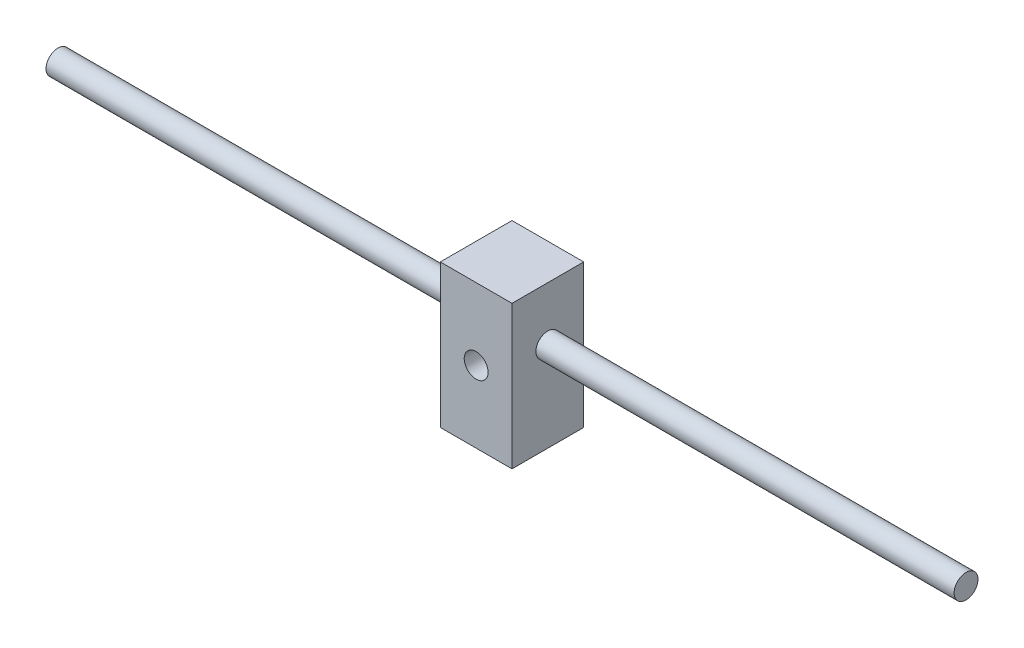
SolidWorks part; units mm, degrees
ref_plane "Спереди" through (0, 0, 0) normal (0, 0, 1) x (1, 0, 0)
ref_plane "Сверху" through (0, 0, 0) normal (0, 1, 0) x (1, 0, 0)
ref_plane "Справа" through (0, 0, 0) normal (1, 0, 0) x (0, 0, -1)
other "Configuration Table"
sketch "Эскиз1" plane through (0, 0, 0) normal (0, 0, 1) x (1, 0, 0)
  line L0 (-30, 0) -> (0, 0) construction
  line L1 (-30, 60) -> (30, 60)
  line L2 (-30, 60) -> (-30, -60)
  line L3 (-30, -60) -> (30, -60)
  line L4 (30, 60) -> (30, -60)
  circle A0 centre (0, 0) radius 10
  point P8 (-30, -30)
  dimension "D1" = 20
  dimension "D2" = 120
  dimension "D3" = 30
  dimension "D4" = 60
extrude "Бобышка-Вытянуть1" add sketch "Эскиз1" along normal mid plane 60
sketch "Эскиз2" plane through (-30, 0, 0) normal (-1, 0, 0) x (0, 0, 1)
  line L0 (0, 15) -> (0, 0) construction
  circle A0 centre (0, 15) radius 10
  point P2 (0, 15.1)
  point P5 (0, 0)
  point P6 (0, 0)
  dimension "D1" = 20
  dimension "D2" = 15
extrude "Бобышка-Вытянуть2" add sketch "Эскиз2" along normal blind 350
sketch "Эскиз3" plane through (30, 0, 0) normal (1, 0, 0) x (0, 0, -1)
  line L0 (0, 15) -> (0, 0) construction
  circle A0 centre (0, 15) radius 10
  dimension "D1" = 20
  dimension "D2" = 15
extrude "Бобышка-Вытянуть3" add sketch "Эскиз3" along normal blind 350
